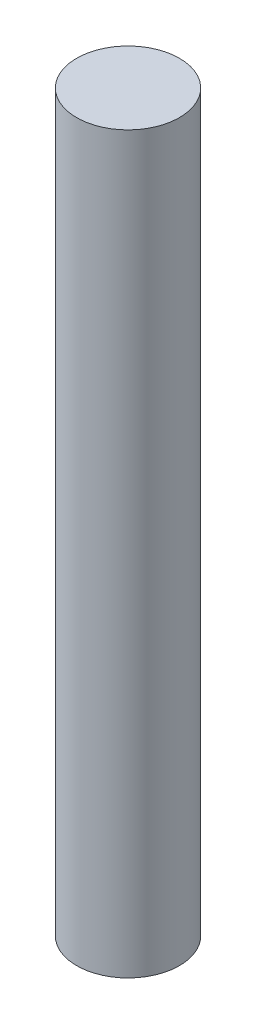
SolidWorks part; units mm, degrees
ref_plane "Front Plane" through (0, 0, 0) normal (0, 0, 1) x (1, 0, 0)
ref_plane "Top Plane" through (0, 0, 0) normal (0, 1, 0) x (1, 0, 0)
ref_plane "Right Plane" through (0, 0, 0) normal (1, 0, 0) x (0, 0, -1)
sketch "Sketch1" plane through (0, 0, 0) normal (0, 1, 0) x (1, 0, 0)
  circle A0 centre (0, 0) radius 10.668
  dimension "D1" = 21.336
extrude "Boss-Extrude1" add sketch "Sketch1" along normal blind 152.4
